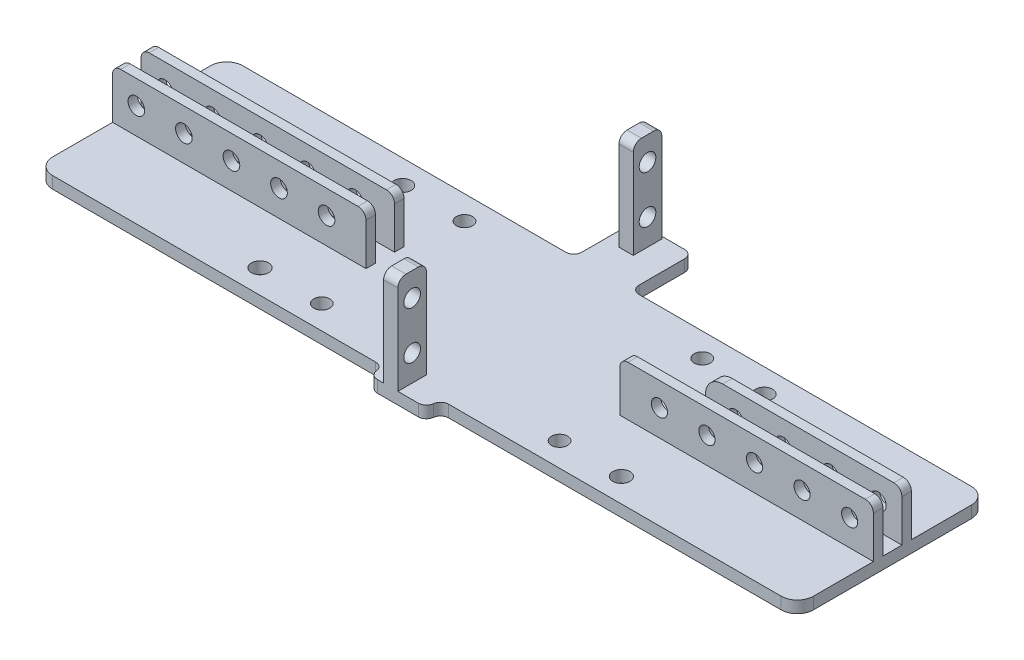
SolidWorks part; units mm, degrees
ref_plane "前视基准面" through (0, 0, 0) normal (0, 0, 1) x (1, 0, 0)
ref_plane "上视基准面" through (0, 0, 0) normal (0, 1, 0) x (1, 0, 0)
ref_plane "右视基准面" through (0, 0, 0) normal (1, 0, 0) x (0, 0, -1)
other "Configuration Table"
sketch "草图1" plane through (0, 0, 0) normal (0, 1, 0) x (1, 0, 0)
  line L0 (0, 0) -> (0, 15) construction
  line L1 (-80, 20) -> (80, 20)
  line L2 (-80, 20) -> (-80, -20)
  line L3 (-80, -20) -> (80, -20)
  line L4 (80, 20) -> (80, -20)
  line L5 (-80, 20) -> (80, -20) construction
  line L6 (-80, -20) -> (80, 20) construction
  line L7 (0, 15) -> (-25, 15) construction
  line L8 (-25, 15) -> (-25, -15) construction
  line L9 (-25, -15) -> (25, -15) construction
  line L10 (25, -15) -> (25, 15) construction
  circle A0 centre (-25, 15) radius 1.7
  circle A1 centre (25, 15) radius 1.7
  circle A2 centre (25, -15) radius 1.7
  circle A3 centre (-25, -15) radius 1.7
  point P0 (0, 0)
  dimension "D7" = 3.4
  dimension "D8" = 3.4
  dimension "D9" = 3.4
  dimension "D10" = 3.4
  dimension "D1" = 40
  dimension "D2" = 160
  dimension "D3" = 15
  dimension "D4" = 25
  dimension "D5" = 30
  dimension "D6" = 50
extrude "凸台-拉伸2" add sketch "草图1" against normal blind 2.5
fillet "圆角2" radius 3.4 4 edges at (-80, -1.25, -20) (-80, -1.25, 20) (80, -1.25, -20) (80, -1.25, 20)
sketch "草图2" plane through (0, 0, 0) normal (0, 1, 0) x (1, 0, 0)
  line L0 (0, 0) -> (0, 20) construction
  line L1 (76.6, 20) -> (-76.6, 20) construction
  line L2 (0, 20) -> (-16, 20) construction
  line L3 (-16, 20) -> (10, 20) construction
  line L4 (10, 20) -> (-16, 20) construction
  line L5 (-16, 20) -> (-16, 15) construction
  line L6 (-16, 20) -> (-16, -20) construction
  line L7 (-76.6, -20) -> (76.6, -20) construction
  line L8 (-16, -20) -> (-16, 29.5) construction
  line L9 (-16, 29.5) -> (-16, 20) construction
  line L10 (-26.7, 15) -> (-23.3, 15) construction
  line L11 (-23.3, 15) -> (-25, 15) construction
  line L12 (-25, 15) -> (-25, 29.5) construction
  line L13 (-25, 29.5) -> (-5, 29.5) construction
  line L14 (-5, 29.5) -> (-1, 29.5) construction
  line L15 (-1, 29.5) -> (-1, -20) construction
  line L16 (-1, -20) -> (-5, -20) construction
  line L17 (-1, 29.5) -> (-1, 20) construction
  line L18 (-1, 20) -> (-1, 24.75) construction
  line L19 (-1, 29.5) -> (-2.5, 29.5) construction
  line L20 (5, 33) -> (-7, 33)
  line L21 (5, 33) -> (5, 16.5)
  line L22 (5, 16.5) -> (-7, 16.5)
  line L23 (-7, 33) -> (-7, 16.5)
  line L24 (5, 33) -> (-7, 16.5) construction
  line L25 (5, 16.5) -> (-7, 33) construction
  line L26 (5, -23) -> (-7, -23)
  line L27 (5, -23) -> (5, -17)
  line L28 (5, -17) -> (-7, -17)
  line L29 (-7, -23) -> (-7, -17)
  line L30 (5, -23) -> (-7, -17) construction
  line L31 (5, -17) -> (-7, -23) construction
  line L32 (-2.5, 29.5) -> (-3, -20) construction
  circle A0 centre (-25, 15) radius 1.7 construction
  dimension "D5" = 20
  dimension "D1" = 16
  dimension "D2" = 26
  dimension "D3" = 5
  dimension "D4" = 49.5
  dimension "D6" = 4
  dimension "D7" = 16.5
  dimension "D8" = 12
  dimension "D9" = 6
  dimension "D10" = 12
  dimension "D11" = 1.5
extrude "凸台-拉伸3" add sketch "草图2" against normal blind 2.5
fillet "圆角4" radius 1.7 4 edges at (5, -1.25, 23) (-7, -1.25, 23) (5, -1.25, -33) (-7, -1.25, -33)
fillet "圆角5" radius 1.7 4 edges at (5, -1.25, 20) (-7, -1.25, 20) (5, -1.25, -20) (-7, -1.25, -20)
sketch "草图3" plane through (0, 0, 0) normal (0, 1, 0) x (1, 0, 0)
  line L0 (-26.7, 15) -> (-23.3, 15) construction
  line L1 (-23.3, 15) -> (-25, 15) construction
  line L2 (-8.6764, -20) -> (6.6764, -20) construction
  line L3 (6.6764, -20) -> (6.6764, 29.5) construction
  line L4 (6.6764, 29.5) -> (-25, 29.5) construction
  line L5 (-25, 29.5) -> (-1, 29.5) construction
  line L6 (-1, 29.5) -> (-2.5, 29.5) construction
  line L7 (-2.5, 29.5) -> (-2.5, -20) construction
  line L9 (-4, 32.5) -> (-1, 32.5)
  line L10 (-4, 32.5) -> (-4, 26.5)
  line L11 (-4, 26.5) -> (-1, 26.5)
  line L12 (-1, 32.5) -> (-1, 26.5)
  line L13 (-4, 32.5) -> (-1, 26.5) construction
  line L14 (-4, 26.5) -> (-1, 32.5) construction
  line L15 (-4, -17) -> (-1, -17)
  line L16 (-4, -17) -> (-4, -23)
  line L17 (-4, -23) -> (-1, -23)
  line L18 (-1, -17) -> (-1, -23)
  line L19 (-4, -17) -> (-1, -23) construction
  line L20 (-4, -23) -> (-1, -17) construction
  line L21 (-5.3, -23) -> (3.3, -23) construction
  circle A0 centre (-25, 15) radius 1.7 construction
  dimension "D1" = 49.5
  dimension "D2" = 24
  dimension "D3" = 1.5
  dimension "D4" = 6
  dimension "D5" = 3
  dimension "D6" = 6
  dimension "D7" = 3
extrude "凸台-拉伸4" add sketch "草图3" along normal blind 20.5
sketch "草图4" plane through (0, 0, 0) normal (1, 0, 0) x (0, 0, -1)
  line L0 (-20, 20.5) -> (-20, 15.5) construction
  line L1 (-23, 20.5) -> (-17, 20.5) construction
  line L2 (-20, 15.5) -> (-20, 5.5) construction
  line L3 (29.5, 20.5) -> (29.5, 15.5) construction
  line L4 (26.5, 20.5) -> (32.5, 20.5) construction
  line L5 (29.5, 15.5) -> (29.5, 5.5) construction
  circle A0 centre (-20, 15.5) radius 1.75
  circle A1 centre (-20, 5.5) radius 1.75
  circle A2 centre (29.5, 15.5) radius 1.75
  circle A3 centre (29.5, 5.5) radius 1.75
  dimension "D5" = 3.5
  dimension "D6" = 3.5
  dimension "D7" = 3.5
  dimension "D8" = 3.5
  dimension "D1" = 5
  dimension "D2" = 10
  dimension "D3" = 5
  dimension "D4" = 10
extrude "切除-拉伸1" cut sketch "草图4" against normal blind 20.5
fillet "圆角6" radius 1.7 4 edges at (-2.5, 20.5, -32.5) (-2.5, 20.5, -26.5) (-2.5, 20.5, 17) (-2.5, 20.5, 23)
sketch "草图5" plane through (0, 0, 0) normal (0, 1, 0) x (1, 0, 0)
  line L0 (0, 0) -> (-80, 0) construction
  line L1 (-80, 16.6) -> (-80, -16.6) construction
  line L2 (-80, 0) -> (-80, 3) construction
  line L3 (-80, 3) -> (-80, -3) construction
  line L4 (-80, -3) -> (80, -3) construction
  line L5 (80, -16.6) -> (80, 16.6) construction
  line L6 (80, -3) -> (80, 3) construction
  line L7 (80, 3) -> (0, 3) construction
  line L8 (0, 3) -> (0, -3) construction
  line L9 (-26.7, 15) -> (-26.7, -15) construction
  line L10 (-26.7, -15) -> (-26.7, 0) construction
  line L11 (-26.7, 0) -> (-26.7, 3) construction
  line L12 (-26.7, 3) -> (-26.7, -3) construction
  line L13 (-26.7, -3) -> (-80, -3) construction
  line L14 (-80, -3) -> (-53.35, -3) construction
  line L15 (-53.35, -3) -> (-53.35, 3) construction
  line L16 (26.7, 15) -> (26.7, -15) construction
  line L17 (26.7, -15) -> (26.7, 0) construction
  line L18 (26.7, 0) -> (26.7, 3) construction
  line L19 (26.7, 3) -> (26.7, -3) construction
  line L20 (26.7, -3) -> (80, -3) construction
  line L21 (80, -3) -> (53.35, -3) construction
  line L22 (53.35, -3) -> (53.35, 3) construction
  line L24 (-26.7, -2) -> (-80, -2)
  line L25 (-26.7, -2) -> (-26.7, -4)
  line L26 (-26.7, -4) -> (-80, -4)
  line L27 (-80, -2) -> (-80, -4)
  line L28 (-26.7, -2) -> (-80, -4) construction
  line L29 (-26.7, -4) -> (-80, -2) construction
  line L30 (-26.7, 2) -> (-80, 2)
  line L31 (-26.7, 2) -> (-26.7, 4)
  line L32 (-26.7, 4) -> (-80, 4)
  line L33 (-80, 2) -> (-80, 4)
  line L34 (-26.7, 2) -> (-80, 4) construction
  line L35 (-26.7, 4) -> (-80, 2) construction
  line L36 (26.7, 2) -> (80, 2)
  line L37 (26.7, 2) -> (26.7, 4)
  line L38 (26.7, 4) -> (80, 4)
  line L39 (80, 2) -> (80, 4)
  line L40 (26.7, 2) -> (80, 4) construction
  line L41 (26.7, 4) -> (80, 2) construction
  line L42 (26.7, -2) -> (80, -2)
  line L43 (26.7, -2) -> (26.7, -4)
  line L44 (26.7, -4) -> (80, -4)
  line L45 (80, -2) -> (80, -4)
  line L46 (26.7, -2) -> (80, -4) construction
  line L47 (26.7, -4) -> (80, -2) construction
  circle A0 centre (-25, 15) radius 1.7 construction
  circle A1 centre (-25, -15) radius 1.7 construction
  circle A2 centre (25, 15) radius 1.7 construction
  circle A3 centre (25, -15) radius 1.7 construction
  dimension "D1" = 3
  dimension "D2" = 6
  dimension "D3" = 6
  dimension "D4" = 2
  dimension "D5" = 2
  dimension "D6" = 2
extrude "凸台-拉伸6" add sketch "草图5" along normal blind 10.5
sketch "草图6" plane through (0, 0, 0) normal (0, 0, 1) x (1, 0, 0)
  line L0 (-80, 10.5) -> (-80, 5.5) construction
  line L1 (-80, 10.5) -> (-80, 0) construction
  line L2 (-80, 5.5) -> (-76.6, 5.5) construction
  line L3 (-80, 5.5) -> (-75, 5.5) construction
  line L4 (80, 10.5) -> (80, 5.5) construction
  line L5 (80, 10.5) -> (80, 0) construction
  line L6 (80, 5.5) -> (75, 5.5) construction
  circle A0 centre (-75, 5.5) radius 1.75
  circle A1 centre (-65, 5.5) radius 1.75
  circle A2 centre (-55, 5.5) radius 1.75
  circle A3 centre (-45, 5.5) radius 1.75
  circle A4 centre (-35, 5.5) radius 1.75
  circle A5 centre (75, 5.5) radius 1.7
  circle A6 centre (65, 5.5) radius 1.7
  circle A7 centre (55, 5.5) radius 1.7
  circle A8 centre (45, 5.5) radius 1.7
  circle A9 centre (35, 5.5) radius 1.7
  dimension "D3" = 5
  dimension "D4" = 3.5
  dimension "D7" = 3.4
  dimension "D1" = 5
  dimension "D2" = 3.4
  dimension "D6" = 5
  dimension "D5" = 5
  dimension "D8" = 5
extrude "切除-拉伸2" cut sketch "草图6" against normal blind 10.5 and the other way blind 10.5
fillet "圆角7" radius 1.7 8 edges at (26.7, 10.5, 3) (26.7, 10.5, -3) (80, 10.5, 3) (80, 10.5, -3) (-26.7, 10.5, 3) (-26.7, 10.5, -3) (-80, 10.5, 3) (-80, 10.5, -3)
sketch "草图7" plane through (0, 0, 0) normal (0, 1, 0) x (1, 0, 0)
  line L0 (-23.3, 15) -> (23.3, 15) construction
  line L1 (23.3, 15) -> (0, 15) construction
  line L2 (0, 15) -> (38, 15) construction
  line L3 (38, 15) -> (-38, 15) construction
  line L4 (-26.7, -15) -> (-38, -15) construction
  line L5 (-38, -15) -> (38, -15) construction
  circle A0 centre (-25, 15) radius 1.7 construction
  circle A1 centre (25, 15) radius 1.7 construction
  circle A2 centre (-25, -15) radius 1.7 construction
  circle A3 centre (38, 15) radius 1.8
  circle A4 centre (38, -15) radius 1.8
  circle A5 centre (-38, 15) radius 1.8
  circle A6 centre (-38, -15) radius 1.8
  dimension "D4" = 3.6
  dimension "D5" = 3.6
  dimension "D6" = 3.6
  dimension "D7" = 3.6
  dimension "D1" = 38
  dimension "D2" = 76
  dimension "D3" = 76
extrude "切除-拉伸3" cut sketch "草图7" against normal blind 10
sketch "草图8" plane through (0, 0, -4) normal (0, 0, -1) x (-1, 0, 0)
  line L0 (-36.7, 5.5) -> (-36.7, 10.5) construction
  line L1 (-78.3, 10.5) -> (-28.4, 10.5) construction
  line L2 (-76.6, 0) -> (-6.7, 0) construction
  line L3 (-36.7, 10.5) -> (-26.7, 10.5)
  line L4 (-36.7, 10.5) -> (-36.7, 0)
  line L5 (-36.7, 0) -> (-26.7, 0)
  line L6 (-26.7, 10.5) -> (-26.7, 0)
  line L7 (-80, 0) -> (-26.7, 0) construction
  line L9 (-36.7, 10.5) -> (-38.7, 10.5)
  line L10 (-36.7, 10.5) -> (-36.7, 0)
  line L11 (-36.7, 0) -> (-38.7, 0)
  line L12 (-38.7, 10.5) -> (-38.7, 0)
  circle A0 centre (-35, 5.5) radius 1.7 construction
  circle M1 centre (-35, 5.5) radius 1.7
  line M6 (-26.7, 0) -> (-26.7, 8.8)
  arc M7 (-26.7, 8.8) -> (-28.4, 10.5) centre (-28.4, 8.8) ccw
  line M8 (-28.4, 10.5) -> (-78.3, 10.5)
  line M11 (-80, 0) -> (-26.7, 0)
  dimension "D1" = 10.5
  dimension "D2" = 2
extrude "切除-拉伸4" cut sketch "草图8" against normal up to surface (2 mm away) contours L12 L4 M8 M11 | L4 M8 M1 M11 M6 M7
fillet "圆角8" radius 3.6 1 edges at (38.7, 10.5, -3)
